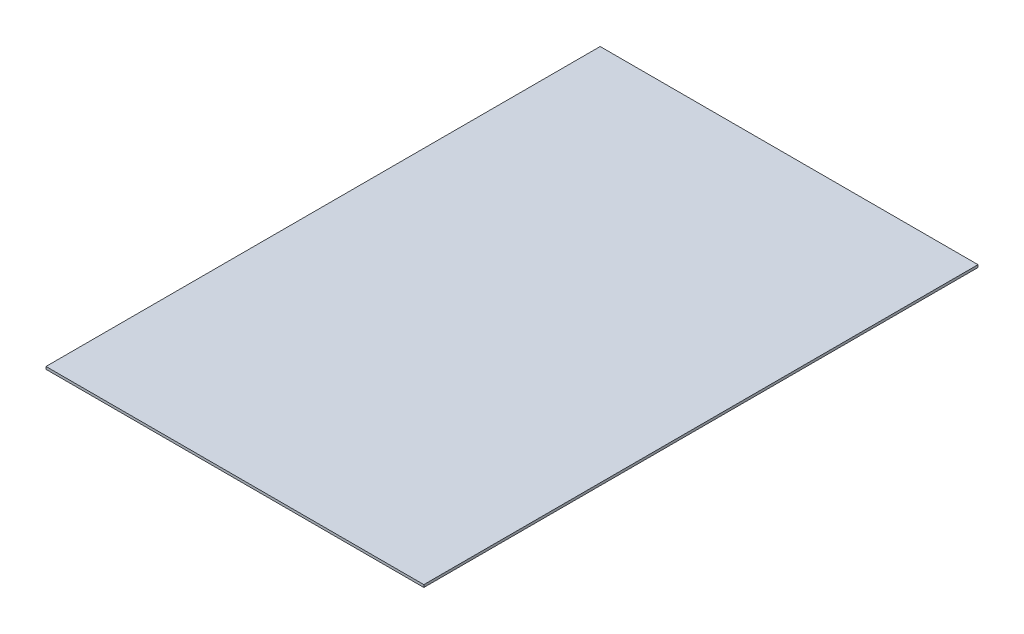
SolidWorks part; units mm, degrees
ref_plane "Front Plane" through (0, 0, 0) normal (0, 0, 1) x (1, 0, 0)
ref_plane "Top Plane" through (0, 0, 0) normal (0, 1, 0) x (1, 0, 0)
ref_plane "Right Plane" through (0, 0, 0) normal (1, 0, 0) x (0, 0, -1)
sketch "Sketch1" plane through (0, 0, 0) normal (0, 1, 0) x (1, 0, 0)
  line L1 (3750, -5500) -> (-3750, -5500)
  line L2 (3750, -5500) -> (3750, 5500)
  line L3 (3750, 5500) -> (-3750, 5500)
  line L4 (-3750, -5500) -> (-3750, 5500)
  line L5 (3750, -5500) -> (-3750, 5500) construction
  line L6 (3750, 5500) -> (-3750, -5500) construction
  point P0 (0, 0)
  dimension "D1" = 7500
  dimension "D2" = 11000
extrude "Boss-Extrude1" add sketch "Sketch1" along normal blind 50
sketch "Sketch2" plane through (0, 0, 0) normal (0, -1, 0) x (1, 0, 0)
  line L0 (0, 5500) -> (0, -5500) construction
  line L1 (-3750, 5500) -> (3750, 5500) construction
  line L2 (3750, -5500) -> (-3750, -5500) construction
  line L3 (3750, 0) -> (-3750, 0) construction
  line L4 (3750, 5500) -> (3750, -5500) construction
  line L5 (-3750, -5500) -> (-3750, 5500) construction
  line L6 (3750, 1250) -> (-3750, 1250) construction
  line L7 (3750, 3000) -> (-3750, 3000) construction
  line L8 (250, 1000) -> (-250, 1000)
  line L9 (250, 1000) -> (250, 1500)
  line L10 (250, 1500) -> (-250, 1500)
  line L11 (-250, 1000) -> (-250, 1500)
  line L12 (250, 1000) -> (-250, 1500) construction
  line L13 (250, 1500) -> (-250, 1000) construction
  line L14 (3750, 5500) -> (0, 5500)
  line L15 (1875, 5500) -> (1875, -5500) construction
  line L16 (0, 5500) -> (-3750, 5500)
  line L17 (-1875, 5500) -> (-1875, -5500) construction
  line L18 (3750, -3000) -> (-3750, -3000) construction
  line L20 (1500, 2625) -> (2250, 2625)
  line L21 (1500, 2625) -> (1500, 3375)
  line L22 (1500, 3375) -> (2250, 3375)
  line L23 (2250, 2625) -> (2250, 3375)
  line L24 (1500, 2625) -> (2250, 3375) construction
  line L25 (1500, 3375) -> (2250, 2625) construction
  line L26 (-2250, 2625) -> (-1500, 2625)
  line L27 (-2250, 2625) -> (-2250, 3375)
  line L28 (-2250, 3375) -> (-1500, 3375)
  line L29 (-1500, 2625) -> (-1500, 3375)
  line L30 (-2250, 2625) -> (-1500, 3375) construction
  line L31 (-2250, 3375) -> (-1500, 2625) construction
  line L32 (-2250, -3375) -> (-1500, -3375)
  line L33 (-2250, -3375) -> (-2250, -2625)
  line L34 (-2250, -2625) -> (-1500, -2625)
  line L35 (-1500, -3375) -> (-1500, -2625)
  line L36 (-2250, -3375) -> (-1500, -2625) construction
  line L37 (-2250, -2625) -> (-1500, -3375) construction
  line L38 (1500, -3375) -> (2250, -3375)
  line L39 (1500, -3375) -> (1500, -2625)
  line L40 (1500, -2625) -> (2250, -2625)
  line L41 (2250, -3375) -> (2250, -2625)
  line L42 (1500, -3375) -> (2250, -2625) construction
  line L43 (1500, -2625) -> (2250, -3375) construction
  point P14 (0, 1250)
  point P31 (1875, 3000)
  point P36 (-1875, 3000)
  point P41 (-1875, -3000)
  point P46 (1875, -3000)
  dimension "D1" = 1250
  dimension "D2" = 500
  dimension "D3" = 500
  dimension "D4" = 2500
  dimension "D5" = 2500
  dimension "D6" = 750
  dimension "D7" = 750
  dimension "D8" = 750
  dimension "D9" = 750
  dimension "D10" = 750
  dimension "D11" = 750
  dimension "D12" = 750
  dimension "D13" = 750
extrude "Cut-Extrude1" cut sketch "Sketch2" against normal blind 10 contours L20 L23 L22 L21 | L26 L29 L28 L27 | L32 L35 L34 L33 | L38 L41 L40 L39 | L10 L11 L8 L9
